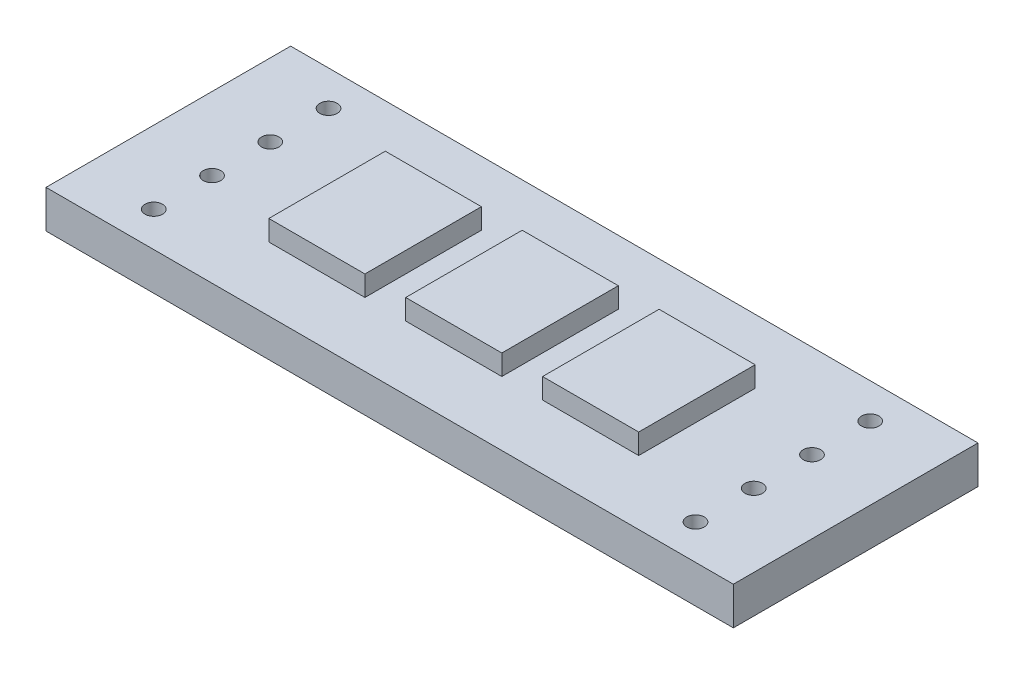
SolidWorks part; units mm, degrees
ref_plane "Front Plane" through (0, 0, 0) normal (0, 0, 1) x (1, 0, 0)
ref_plane "Top Plane" through (0, 0, 0) normal (0, 1, 0) x (1, 0, 0)
ref_plane "Right Plane" through (0, 0, 0) normal (1, 0, 0) x (0, 0, -1)
sketch "Sketch1" plane through (0, 0, 0) normal (0, 1, 0) x (1, 0, 0)
  line L1 (0, 0) -> (29.972, 0)
  line L2 (0, 0) -> (0, 10.668)
  line L3 (0, 10.668) -> (29.972, 10.668)
  line L4 (29.972, 0) -> (29.972, 10.668)
  dimension "D1" = 29.972
  dimension "D2" = 10.668
extrude "Boss-Extrude1" add sketch "Sketch1" along normal blind 1.651
sketch "Sketch2" plane through (0, 1.651, 0) normal (0, 1, 0) x (1, 0, 0)
  line L0 (14.986, 10.668) -> (14.986, 0) construction
  line L1 (29.972, 10.668) -> (0, 10.668) construction
  line L2 (0, 0) -> (29.972, 0) construction
  line L3 (17.0815, 7.874) -> (12.8905, 7.874)
  line L4 (12.8905, 7.874) -> (12.8905, 2.794)
  line L5 (12.8905, 2.794) -> (17.0815, 2.794)
  line L6 (0, 5.334) -> (29.972, 5.334) construction
  line L7 (0, 10.668) -> (0, 0) construction
  line L8 (29.972, 0) -> (29.972, 10.668) construction
  line L9 (17.0815, 7.874) -> (17.0815, 2.794)
  line L10 (11.1125, 7.874) -> (6.9215, 7.874)
  line L11 (11.1125, 7.874) -> (11.1125, 2.794)
  line L12 (11.1125, 2.794) -> (6.9215, 2.794)
  line L13 (6.9215, 7.874) -> (6.9215, 2.794)
  line L14 (18.8595, 7.874) -> (18.8595, 2.794)
  line L15 (18.8595, 2.794) -> (23.0505, 2.794)
  line L16 (23.0505, 7.874) -> (23.0505, 2.794)
  line L17 (18.8595, 7.874) -> (23.0505, 7.874)
  point P21 (14.986, 7.874)
  point P22 (14.986, 2.794)
  dimension "D1" = 5.08
  dimension "D2" = 2.54
  dimension "D3" = 2.0955
  dimension "D4" = 4.191
  dimension "D5" = 1.778
  dimension "D6" = 5.08
extrude "Boss-Extrude2" add sketch "Sketch2" along normal blind 0.889
sketch "Sketch3" plane through (0, 1.651, 0) normal (0, 1, 0) x (1, 0, 0)
  line L0 (29.972, 5.334) -> (0, 5.334) construction
  line L1 (29.972, 0) -> (29.972, 10.668) construction
  line L2 (0, 10.668) -> (0, 0) construction
  line L3 (14.986, 0) -> (14.986, 10.668) construction
  line L4 (0, 0) -> (29.972, 0) construction
  line L5 (29.972, 10.668) -> (0, 10.668) construction
  circle A0 centre (26.797, 1.524) radius 0.381
  circle A1 centre (26.797, 4.064) radius 0.381
  circle A2 centre (26.797, 6.604) radius 0.381
  circle A3 centre (26.797, 9.144) radius 0.381
  circle A4 centre (3.175, 1.524) radius 0.381
  circle A5 centre (3.175, 4.064) radius 0.381
  circle A6 centre (3.175, 6.604) radius 0.381
  circle A7 centre (3.175, 9.144) radius 0.381
  dimension "D3" = 0.762
  dimension "D4" = 0.762
  dimension "D1" = 3.81
  dimension "D2" = 1.27
  dimension "D5" = 3.175
  dimension "D6" = 3.175
extrude "Cut-Extrude1" cut sketch "Sketch3" against normal through all
